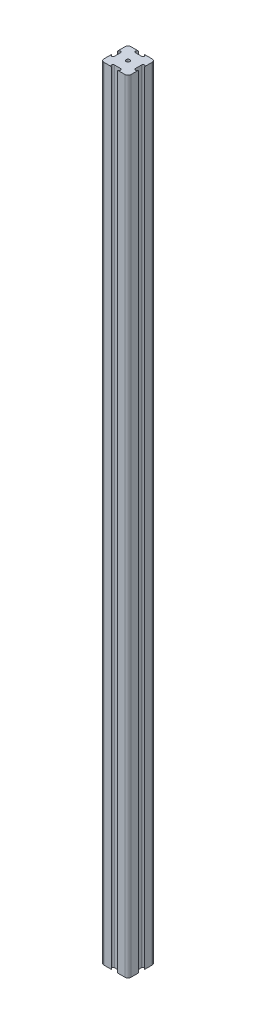
SolidWorks part; units mm, degrees
ref_plane "Front Plane" through (0, 0, 0) normal (0, 0, 1) x (1, 0, 0)
ref_plane "Top Plane" through (0, 0, 0) normal (0, 1, 0) x (1, 0, 0)
ref_plane "Right Plane" through (0, 0, 0) normal (1, 0, 0) x (0, 0, -1)
sketch "Esquisse4" plane through (0, 0, 0) normal (0, 1, 0) x (1, 0, 0)
  line L0 (-17.5, 22.5) -> (-5, 22.5)
  line L1 (22.5, 5) -> (22.5, 17.5)
  line L2 (0, 0) -> (22.5, 0) construction
  line L3 (5, 22.5) -> (17.5, 22.5)
  line L4 (0, 22.5) -> (0, 0) construction
  line L5 (-5, -17.5) -> (5, -17.5)
  line L6 (5, -22.5) -> (17.5, -22.5)
  line L7 (17.5, 5) -> (17.5, -5)
  line L8 (-5, -22.5) -> (-17.5, -22.5)
  line L10 (-5, 20) -> (5, 20) construction
  line L11 (0, 0) -> (0, -28.4326) construction
  line L12 (-5, 17.5) -> (5, 17.5)
  line L13 (17.5, 22.5) -> (17.5, -22.5) construction
  line L14 (-22.5, 17.5) -> (-22.5, 5)
  line L15 (-22.5, -5) -> (-22.5, -17.5)
  line L17 (-17.5, 5) -> (-17.5, -5)
  line L18 (0, 0) -> (-28.2169, 0) construction
  line L19 (22.5, -5) -> (22.5, -17.5)
  arc A0 (17.5, 22.5) -> (22.5, 17.5) centre (17.5, 17.5) cw
  arc A1 (17.5, -22.5) -> (22.5, -17.5) centre (17.5, -17.5) ccw
  arc A2 (-22.5, -17.5) -> (-17.5, -22.5) centre (-17.5, -17.5) ccw
  arc A3 (-17.5, 22.5) -> (-22.5, 17.5) centre (-17.5, 17.5) ccw
  arc A5 (-5, 22.5) -> (-5, 17.5) centre (-5, 20) ccw
  arc A6 (5, 17.5) -> (5, 22.5) centre (5, 20) ccw
  arc A7 (-5, -17.5) -> (-5, -22.5) centre (-5, -20) ccw
  arc A8 (5, -22.5) -> (5, -17.5) centre (5, -20) ccw
  arc A9 (-17.5, -5) -> (-22.5, -5) centre (-20, -5) cw
  arc A10 (22.5, -5) -> (17.5, -5) centre (20, -5) cw
  arc A11 (-17.5, 5) -> (-22.5, 5) centre (-20, 5) ccw
  arc A12 (22.5, 5) -> (17.5, 5) centre (20, 5) ccw
  point P8 (22.5, 22.5)
  point P13 (0, -17.5)
  point P20 (-22.5, 22.5)
  point P23 (0, 20)
  point P44 (0, 0)
  point P45 (0, 0)
  point P46 (0, 0)
  point P47 (28.2853, -8.4459)
  point P51 (0, 0)
  point P52 (0, 0)
  point P53 (-22.5, 5)
  point P54 (-17.5, 5)
  point P55 (-22.5, 5)
  point P56 (17.5, -7.7525)
  point P58 (0, 0)
  point P59 (22.5, -5)
  point P60 (17.5, 5)
  point P61 (22.5, 5)
  point P62 (20, -5)
  point P63 (17.5, -5)
  point P64 (22.5, -5)
  point P65 (17.5, 5)
  point P66 (22.5, 5)
  point P67 (22.5, -5)
  point P68 (17.5, -5)
  point P69 (0, 0)
  dimension "D4" = 5
  dimension "D6" = 5
  dimension "D7" = 5
  dimension "D8" = 5
  dimension "D20" = 10
  dimension "D24" = 12.5
  dimension "D2" = 22.5
  dimension "D3" = 45
  dimension "D5" = 10
  dimension "D10" = 10
  dimension "D11" = 12.5
  dimension "D12" = 22.5
  dimension "D13" = 5
  dimension "D14" = 17.5
  dimension "D15" = 12.5
  dimension "D16" = 45
  dimension "D17" = 2.5
  dimension "D18" = 5
  dimension "D19" = 45
  dimension "D21" = 5
  dimension "D22" = 17.5
  dimension "D23" = 10
  dimension "D25" = 5
extrude "Boss.-Extru.2" add sketch "Esquisse4" along normal blind 1300 contours L15 A2 L8 A7 L5 A8 L6 A1 L19 A10 L7 A12 L1 A0 L3 A6 L12 A5 L0 A3 L14 A11 L17 A9
sketch "Esquisse5" plane through (0, 0, 0) normal (0, -1, 0) x (1, 0, 0)
  circle A0 centre (0, 0) radius 3
extrude "Enlèv. mat.-Extru.1" cut sketch "Esquisse5" against normal through all
